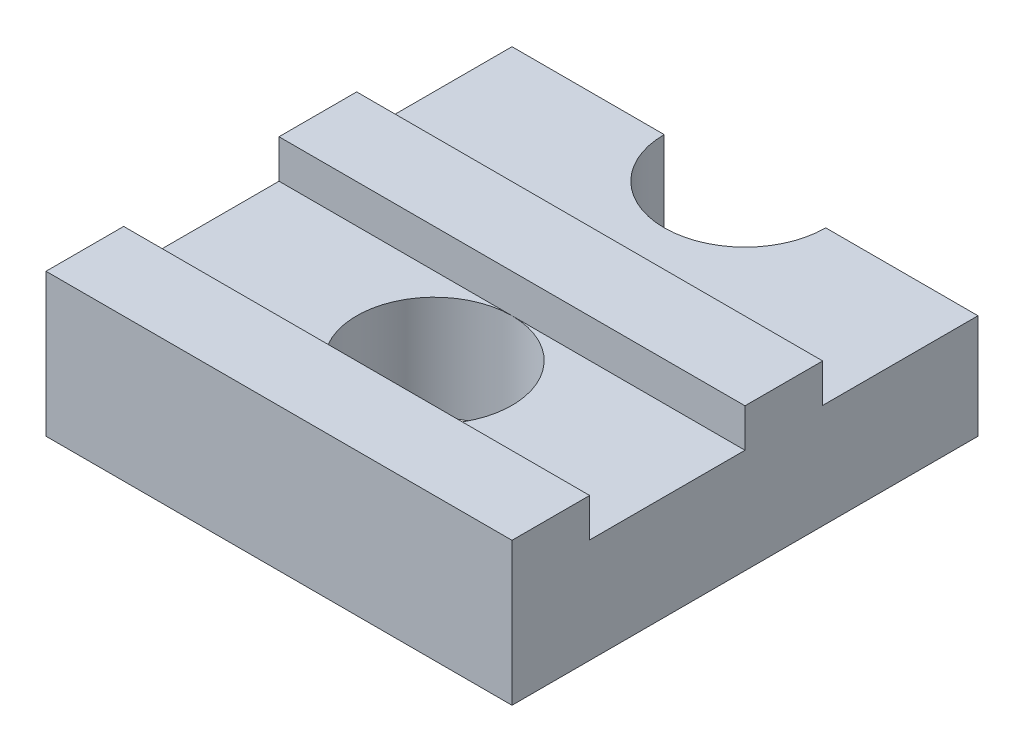
SolidWorks part; units mm, degrees
ref_plane "Front Plane" through (0, 0, 0) normal (0, 0, 1) x (1, 0, 0)
ref_plane "Top Plane" through (0, 0, 0) normal (0, 1, 0) x (1, 0, 0)
ref_plane "Right Plane" through (0, 0, 0) normal (1, 0, 0) x (0, 0, -1)
sketch "Sketch1" plane through (0, 0, 0) normal (0, 1, 0) x (1, 0, 0)
  line L1 (4.7625, -4.7625) -> (-4.7625, -4.7625)
  line L2 (4.7625, -4.7625) -> (4.7625, 4.7625)
  line L3 (4.7625, 4.7625) -> (-4.7625, 4.7625)
  line L4 (-4.7625, -4.7625) -> (-4.7625, 4.7625)
  line L5 (4.7625, -4.7625) -> (-4.7625, 4.7625) construction
  line L6 (4.7625, 4.7625) -> (-4.7625, -4.7625) construction
  point P0 (0, 0)
  dimension "D1" = 9.525
  dimension "D2" = 9.525
extrude "Boss-Extrude1" add sketch "Sketch1" along normal blind 2.921
sketch "Sketch2" plane through (0, 2.921, 0) normal (0, 1, 0) x (1, 0, 0)
  line L0 (-4.7625, 4.7625) -> (-4.7625, -4.7625) construction
  line L1 (4.7625, -3.175) -> (-4.7625, -3.175)
  line L2 (4.7625, -3.175) -> (4.7625, 0)
  line L3 (4.7625, 0) -> (-4.7625, 0)
  line L4 (-4.7625, -3.175) -> (-4.7625, 0)
  line L5 (4.7625, -3.175) -> (-4.7625, 0) construction
  line L6 (4.7625, 0) -> (-4.7625, -3.175) construction
  line L7 (-4.7625, -4.7625) -> (4.7625, -4.7625) construction
  line L8 (4.7625, 1.5875) -> (-4.7625, 1.5875)
  line L9 (4.7625, 1.5875) -> (4.7625, 4.7625)
  line L10 (4.7625, 4.7625) -> (-4.7625, 4.7625)
  line L11 (-4.7625, 1.5875) -> (-4.7625, 4.7625)
  line L12 (4.7625, 1.5875) -> (-4.7625, 4.7625) construction
  line L13 (4.7625, 4.7625) -> (-4.7625, 1.5875) construction
  point P0 (0, -1.5875)
  point P7 (0, 3.175)
  dimension "D1" = 4.7625
  dimension "D2" = 6.35
  dimension "D3" = 1.5875
extrude "Cut-Extrude1" cut sketch "Sketch2" against normal blind 0.7874
sketch "Sketch3" plane through (0, 2.1336, 0) normal (0, 1, 0) x (1, 0, 0)
  line L0 (-4.7625, -4.7625) -> (4.7625, -4.7625) construction
  line L1 (-4.7625, 0) -> (-4.7625, -3.175) construction
  line L2 (4.7625, 4.7625) -> (-4.7625, 4.7625) construction
  line L3 (-1.651, 4.7625) -> (1.651, 4.7625)
  circle A0 centre (0, -1.5875) radius 1.5875
  arc A1 (-1.651, 4.7625) -> (1.651, 4.7625) centre (0, 4.7625) ccw
  dimension "D1" = 3.175
  dimension "D2" = 3.175
  dimension "D3" = 4.7625
extrude "Cut-Extrude2" cut sketch "Sketch3" against normal through all
